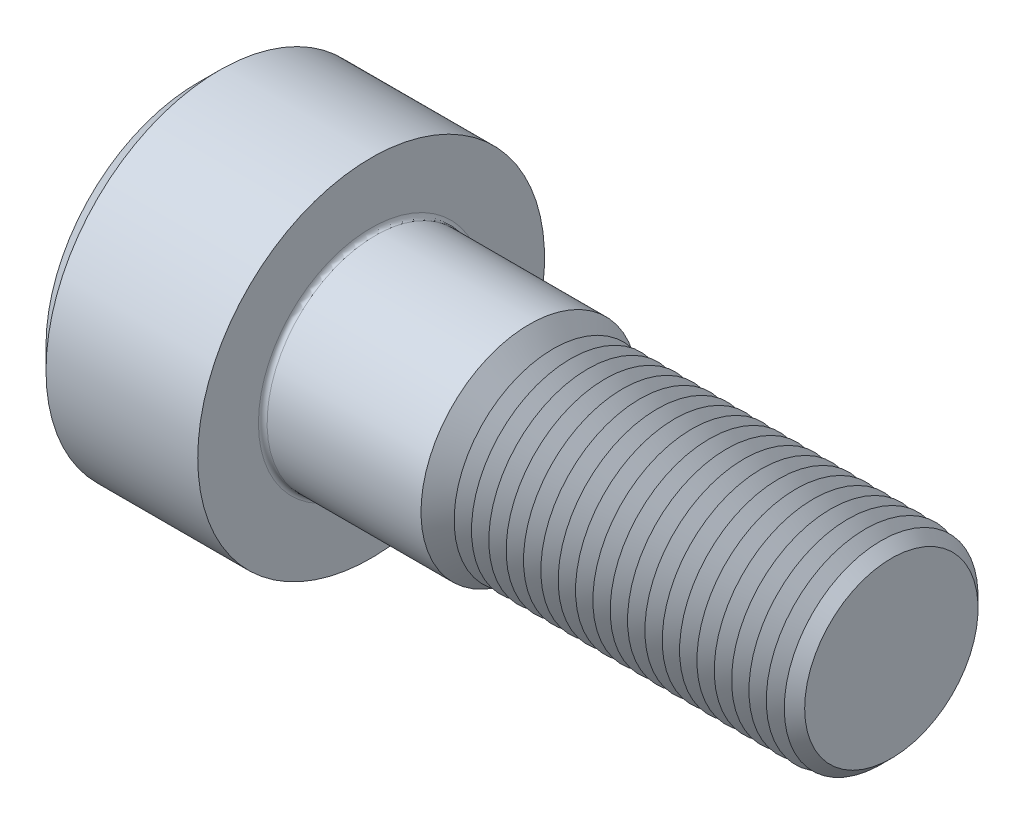
SolidWorks part; units mm, degrees
revolve "Base-Revolve" add sketch "BodySke"
sketch "BodySke" plane through (0, 0, 0) normal (0, 0, 1) x (1, 0, 0)
  line L0 (0, 0) -> (0, 3.5)
  line L1 (0.5, 4) -> (4, 4)
  line L2 (4, 4) -> (4, 2.5)
  line L3 (4, 2.5) -> (15.5, 2.5)
  line L4 (16, 2) -> (16, 0)
  line L5 (16, 0) -> (0, 0)
  line L6 (-31.75, 0) -> (127, 0) construction
  line L7 (0, 3.5) -> (0.5, 4)
  line L8 (16, 2) -> (15.5, 2.5)
  line L9 (0, -3.5) -> (0.5, -4) construction
  line L10 (16, -2) -> (15.5, -2.5) construction
  line L11 (4.4, 9.525) -> (4.4, 3.175) construction
  line L12 (8, 9.525) -> (8, 3.175) construction
  line L13 (-34, 9.525) -> (-34, 3.175) construction
  dimension "Diameter" = 5
  dimension "Head_ht" = 4
  dimension "Length" = 12
  dimension "Body_ch_ang" = 45
  dimension "Head_dia" = 8
  dimension "Head_ch_ang" = 45
  dimension "Minor_dia" = 4
  dimension "Advance" = 0.4
  dimension "Thread_nom" = 8
  dimension "Thread_length" = 50
  dimension "Head_ch_ht" = 0.5
cosmetic thread "ThreadCosmetic" [suppressed]
fillet "Fillet1" radius 0.1 1 edges at (4, 0, 2.5)
ref_plane "Plane1" through (0, 0, 0) normal (0, 0, 1) x (1, 0, 0)
ref_plane "Plane2" through (0, 0, 0) normal (0, 1, 0) x (1, 0, 0)
ref_plane "Plane3" through (0, 0, 0) normal (1, 0, 0) x (0, 0, -1)
sketch "Sketch2" plane through (0, 0, 0) normal (0, 0, 1) x (1, 0, 0)
  line L0 (0, 0.7725) -> (1, 0.7725)
  line L1 (1, 0.7725) -> (1.446, 0)
  line L2 (-31.75, 0) -> (127, 0) construction
  line L3 (1.446, 0) -> (0, 0)
  line L4 (0, 0) -> (0, 0.7725)
  line L5 (0, 3.5) -> (0, -3.5) construction
  line L6 (0, 0) -> (47.625, 0) construction
  line L7 (4, -4) -> (4, 4) construction
  dimension "D1" = 0.7725
  dimension "D2" = 60
revolve "Hex-PreBroach" cut sketch "Sketch2" angle 360 about L6
sketch "Sketch3" plane through (0, 0, 0) normal (-1, 0, 0) x (0, 0.5, 0.866)
  line L0 (0.446, 0.7725) -> (-0.446, 0.7725)
  line L1 (-0.446, 0.7725) -> (-0.892, 0)
  line L2 (0.446, 0.7725) -> (0.892, 0)
  line L3 (0.446, -0.7725) -> (0.892, 0)
  line L4 (0.446, -0.7725) -> (-0.446, -0.7725)
  line L5 (-0.446, -0.7725) -> (-0.892, 0)
  dimension "D1" = 0.7725
  dimension "D2" = 0.7725
  dimension "Hex_size" = 1.545
extrude "Hex" cut sketch "Sketch3" against normal blind 1
sketch "Sketch4" plane through (0, 0, 0) normal (-1, 0, 0) x (0, 0, 1)
  line L0 (0, 0) -> (0.9398, 0)
  line L1 (0, 0) -> (6.1484, 3.5498) construction
  line L2 (0, 0) -> (0.4699, 0.8139)
  line L3 (0.7832, 0.2175) -> (0.8962, 0.2828)
  line L4 (0.58, 0.5695) -> (0.693, 0.6348)
  arc A0 (0.7832, 0.2175) -> (0.58, 0.5695) centre (0, 0) ccw
  arc A1 (0.9398, 0) -> (0.8962, 0.2828) centre (0, 0) ccw
  arc A2 (0.4699, 0.8139) -> (0.693, 0.6348) centre (0, 0) cw
  dimension "D1" = 30
  dimension "D2" = 60
  dimension "Spline_p_dim" = 0.4064
  dimension "D3" = 0.2032
extrude "Spline" [suppressed] cut sketch "Sketch4" against normal blind 1
pattern_circular "CirPattern1" [suppressed] count 6 every 60
sketch "Sketch5" plane through (0, 0, 0) normal (0, 0, 1) x (1, 0, 0)
  line L0 (-31.75, 0) -> (127, 0) construction
  line L2 (0, 3.5) -> (0, -3.5) construction
  circle A0 centre (0.1, 0) radius 0.005
  dimension "Drilled_hole_dia" = 0.01
  dimension "Drilled_hole_loc" = 0.1
extrude "Hole" [suppressed] cut sketch "Sketch5" against normal through all and the other way through all
pattern_circular "Drilled-4" [suppressed] count 2 every 60
pattern_circular "Drilled-6" [suppressed] count 3 every 60
sketch "ThdSchSke" plane through (0, 0, 0) normal (0, 0, 1) x (1, 0, 0)
  line L0 (8, -2) -> (7.6499, -2.5)
  line L1 (8, -2) -> (8.3501, -2.5)
  line L2 (8.3501, -2.5) -> (8.3501, -3.125)
  line L3 (-3.175, 0) -> (5.1513, 0) construction
  line L5 (8.3501, -3.125) -> (7.6499, -3.125)
  line L6 (7.6499, -3.125) -> (7.6499, -2.5)
  line L7 (0, 3.5) -> (0, -3.5) construction
  dimension "Thread_minor" = 4
  dimension "Diameter" = 5
  dimension "Start" = 8
revolve "ThreadSchematic" cut sketch "ThdSchSke" angle 360 about L3
pattern_linear "ThdSchPat" count 20 spacing 0.4 along (1, 0, 0) of "ThreadSchematic"
equation "\"D2@Sketch3\" = \"Hex_size@Sketch3\" / 2"
equation "\"D1@Sketch3\" = \"Hex_size@Sketch3\" / 2"
equation "\"D1@Sketch2\" = \"Hex_size@Sketch3\" / 2"
equation "\"D3@Sketch4\" = \"Spline_p_dim@Sketch4\" / 2"
equation "\"Thread_minor@ThreadCosmetic\"  =  \"Minor_dia@BodySke\""
equation "\"D2@CirPattern1\" = 360 / \"Num_teeth@CirPattern1\""
equation "\"Wall_thickness@Sketch2\" = \"Head_ht@BodySke\" - \"Key_eng@Hex\""
equation "\"Thread_length@ThreadCosmetic\" = ((sgn( (\"Length@BodySke\" - \"Advance@BodySke\" ) - \"Thread_nom@BodySke\" )-1)*( (\"Length@BodySke\" - \"Advance@BodySke\" ) - \"Thread_nom@BodySke\" ))/-2+ \"Thread_nom@BodySke\""
equation "\"Thread_minor@ThdSchSke\" = \"Minor_dia@BodySke\""
equation "\"Diameter@ThdSchSke\" = \"Diameter@BodySke\""
equation "\"Overcut@ThdSchSke\" = \"Diameter@BodySke\" * 1.25"
equation "\"Start@ThdSchSke\" = \"Head_ht@BodySke\" + \"Length@BodySke\" - \"Thread_length@ThreadCosmetic\"  '---Non-countersunk---"
equation "\"Num_threads@ThdSchPat\" = int( \"Thread_length@ThreadCosmetic\" / \"Advance@BodySke\" + 0.999 )  + 1"
equation "\"Advance@ThdSchPat\" = \"Thread_length@ThreadCosmetic\" /  (\"Num_threads@ThdSchPat\" - 1) 'relax it"
equation "\"Num_threads@ThdSchPat\" = \"Num_threads@ThdSchPat\" - sgn( \"Num_threads@ThdSchPat\" - 1) '---chamfered tips only---"
